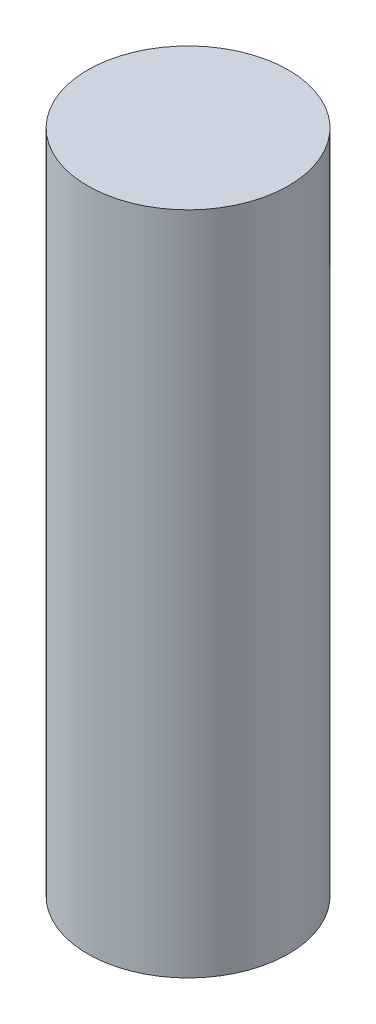
SolidWorks part; units mm, degrees
ref_plane "Front Plane" through (0, 0, 0) normal (0, 0, 1) x (1, 0, 0)
ref_plane "Top Plane" through (0, 0, 0) normal (0, 1, 0) x (1, 0, 0)
ref_plane "Right Plane" through (0, 0, 0) normal (1, 0, 0) x (0, 0, -1)
sketch "Sketch2" plane through (0, 0, 0) normal (0, 1, 0) x (1, 0, 0)
  circle A0 centre (0, 0) radius 23
  arc A1 (-17.7474, -14.6297) -> (17.7474, 14.6297) centre (0, 0) ccw construction
extrude "Boss-Extrude1" add sketch "Sketch2" along normal blind 152.4
ref_point "Tool"
